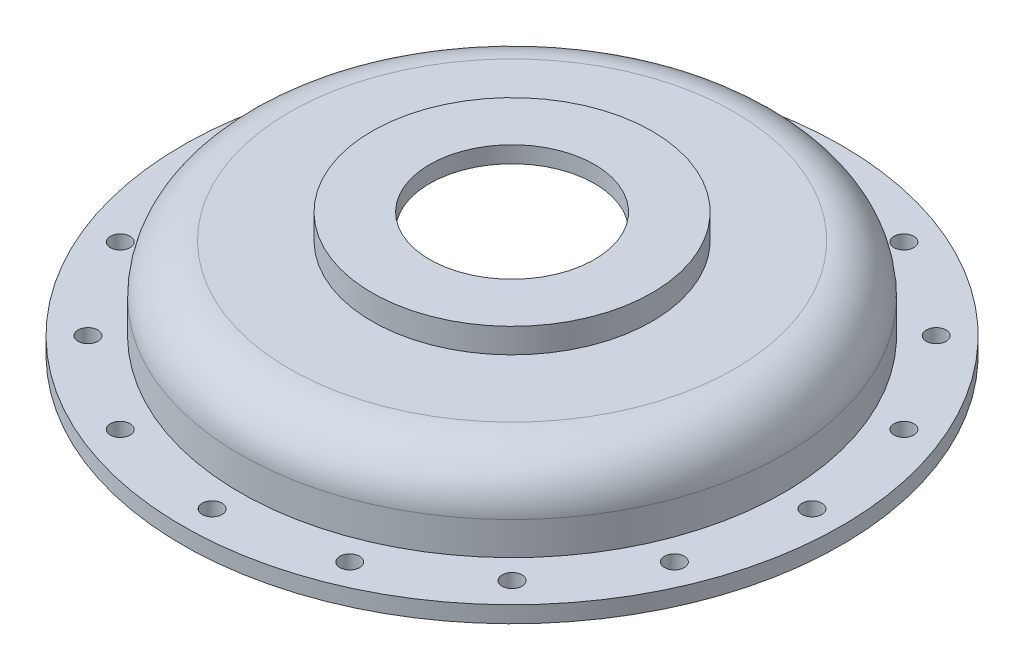
SolidWorks part; units mm, degrees
material "Brass"
ref_plane "Front Plane" through (0, 0, 0) normal (0, 0, 1) x (1, 0, 0)
ref_plane "Top Plane" through (0, 0, 0) normal (0, 1, 0) x (1, 0, 0)
ref_plane "Right Plane" through (0, 0, 0) normal (1, 0, 0) x (0, 0, -1)
sketch "Sketch1" plane through (0, 0, 0) normal (0, 0, 1) x (1, 0, 0)
  line L0 (0, 0) -> (0, 101.7632) construction
  line L1 (-200, 10) -> (-165, 10)
  line L2 (-165, 10) -> (-165, 30)
  line L3 (-135, 60) -> (-85, 60)
  line L4 (-85, 60) -> (-85, 75)
  line L5 (-85, 75) -> (-50, 75)
  line L6 (-200, 0) -> (-155, 0)
  line L7 (-155, 0) -> (-155, 30)
  line L8 (-135, 50) -> (-75, 50)
  line L9 (-75, 50) -> (-75, 65)
  line L10 (-75, 65) -> (-50, 65)
  line L11 (-200, 10) -> (-200, 0)
  line L12 (-50, 75) -> (-50, 65)
  arc A0 (-165, 30) -> (-135, 60) centre (-135, 30) cw
  arc A1 (-155, 30) -> (-135, 50) centre (-135, 30) cw
  dimension "D5" = 30
  dimension "D1" = 75
  dimension "D2" = 330
  dimension "D3" = 400
  dimension "D4" = 15
  dimension "D6" = 10
  dimension "D7" = 100
  dimension "D8" = 170
  dimension "D9" = 10
revolve "Revolve2" add sketch "Sketch1" angle 360 about L0
sketch "Sketch2" plane through (0, 10, 0) normal (0, 1, 0) x (1, 0, 0)
  line L0 (0, 182) -> (0, 0) construction
  circle A2 centre (0, 182) radius 6
  dimension "D1" = 12
  dimension "D2" = 182
extrude "Cut-Extrude8" cut sketch "Sketch2" against normal through all contours A2
pattern_circular "CirPattern1" count 16 over 360 about axis through (0, 0, 0) along (0, 1, 0) of "Cut-Extrude8"
